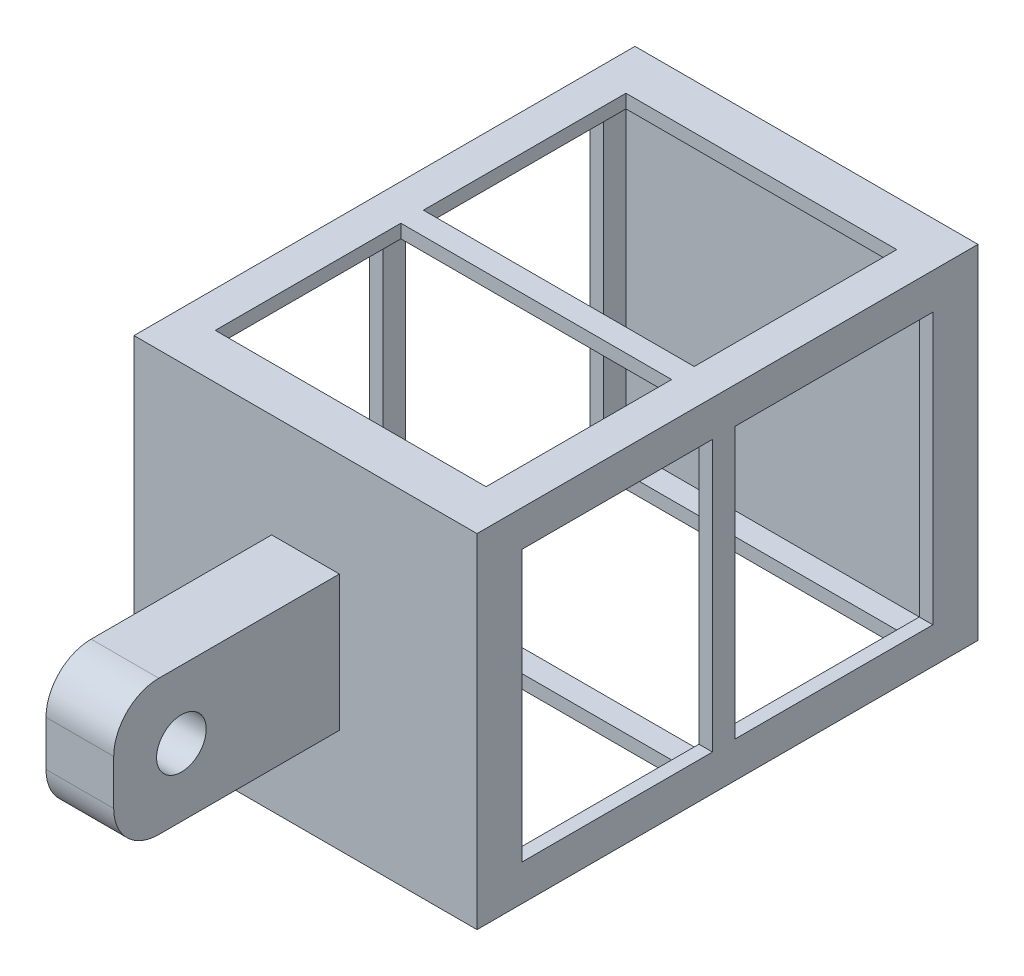
SolidWorks part; units mm, degrees
ref_plane "Plan de face" through (0, 0, 0) normal (0, 0, 1) x (1, 0, 0)
ref_plane "Plan de dessus" through (0, 0, 0) normal (0, 1, 0) x (1, 0, 0)
ref_plane "Plan de droite" through (0, 0, 0) normal (1, 0, 0) x (0, 0, -1)
sketch "Esquisse1" plane through (0, 0, 0) normal (0, 0, 1) x (1, 0, 0)
  line L1 (-33.9569, 29.5307) -> (36.0431, 29.5307)
  line L2 (-33.9569, 29.5307) -> (-33.9569, -40.4693)
  line L3 (-33.9569, -40.4693) -> (36.0431, -40.4693)
  line L4 (36.0431, 29.5307) -> (36.0431, -40.4693)
  line L5 (-36.9569, 32.5307) -> (39.0431, 32.5307)
  line L6 (-36.9569, 32.5307) -> (-36.9569, -43.4693)
  line L7 (-36.9569, -43.4693) -> (39.0431, -43.4693)
  line L8 (39.0431, 32.5307) -> (39.0431, -43.4693)
  dimension "D1" = 70
  dimension "D2" = 70
  dimension "D3" = 3
  dimension "D4" = 3
  dimension "D5" = 3
  dimension "D6" = 3
extrude "Boss.-Extru.2" add sketch "Esquisse1" along normal blind 101
sketch "Esquisse2" plane through (0, 0, 101) normal (0, 0, 1) x (1, 0, 0)
  line L1 (-36.9569, 32.5307) -> (39.0431, 32.5307)
  line L2 (-36.9569, 32.5307) -> (-36.9569, -43.4693)
  line L3 (-36.9569, -43.4693) -> (39.0431, -43.4693)
  line L4 (39.0431, 32.5307) -> (39.0431, -43.4693)
extrude "Boss.-Extru.3" add sketch "Esquisse2" along normal blind 5
sketch "Esquisse3" plane through (0, 0, 0) normal (0, 0, -1) x (-1, 0, 0)
  line L1 (-39.0431, 32.5307) -> (36.9569, 32.5307)
  line L2 (-39.0431, 32.5307) -> (-39.0431, -43.4693)
  line L3 (-39.0431, -43.4693) -> (36.9569, -43.4693)
  line L4 (36.9569, 32.5307) -> (36.9569, -43.4693)
extrude "Boss.-Extru.4" add sketch "Esquisse3" along normal blind 5
sketch "Esquisse4" plane through (0, 32.5307, 0) normal (0, 1, 0) x (1, 0, 0)
  line L0 (36.0431, 0) -> (-33.9569, 0) construction
  line L1 (-28.9569, -5) -> (31.0431, -5)
  line L2 (-28.9569, -5) -> (-28.9569, -49.8788)
  line L3 (-28.9569, -49.8788) -> (31.0431, -49.8788)
  line L4 (31.0431, -5) -> (31.0431, -49.8788)
  line L5 (-28.9569, -54.8788) -> (31.0431, -54.8788)
  line L6 (-28.9569, -54.8788) -> (-28.9569, -96)
  line L7 (-28.9569, -96) -> (31.0431, -96)
  line L8 (31.0431, -54.8788) -> (31.0431, -96)
  line L9 (36.0431, -101) -> (-33.9569, -101) construction
  line L10 (-33.9569, -101) -> (-33.9569, 0) construction
  line L11 (36.0431, -101) -> (36.0431, 0) construction
  dimension "D1" = 5
  dimension "D2" = 5
  dimension "D3" = 5
  dimension "D4" = 5
  dimension "D5" = 5
  dimension "D6" = 5
  dimension "D7" = 5
extrude "Enlèv. mat.-Extru.1" cut sketch "Esquisse4" against normal blind 80
sketch "Esquisse5" plane through (-36.9569, 0, 0) normal (-1, 0, 0) x (0, 0, 1)
  line L0 (101, 29.5307) -> (0, 29.5307) construction
  line L1 (5, 24.5307) -> (48.8322, 24.5307)
  line L2 (5, 24.5307) -> (5, -35.4693)
  line L3 (5, -35.4693) -> (48.8322, -35.4693)
  line L4 (48.8322, 24.5307) -> (48.8322, -35.4693)
  line L5 (53.8322, 24.5307) -> (96, 24.5307)
  line L6 (53.8322, 24.5307) -> (53.8322, -35.4693)
  line L7 (53.8322, -35.4693) -> (96, -35.4693)
  line L8 (96, 24.5307) -> (96, -35.4693)
  line L9 (101, -40.4693) -> (0, -40.4693) construction
  line L10 (0, 29.5307) -> (0, -40.4693) construction
  line L11 (101, 29.5307) -> (101, -40.4693) construction
  dimension "D1" = 5
  dimension "D2" = 5
  dimension "D3" = 5
  dimension "D4" = 5
  dimension "D5" = 5
  dimension "D6" = 5
  dimension "D7" = 5
extrude "Enlèv. mat.-Extru.2" cut sketch "Esquisse5" against normal blind 80
sketch "Esquisse8" plane through (0, 0, 106) normal (0, 0, 1) x (1, 0, 0)
  line L1 (-6.4569, 9.5307) -> (8.5431, 9.5307)
  line L2 (-6.4569, 9.5307) -> (-6.4569, -20.4693)
  line L3 (-6.4569, -20.4693) -> (8.5431, -20.4693)
  line L4 (8.5431, 9.5307) -> (8.5431, -20.4693)
  line L5 (-36.9569, -43.4693) -> (39.0431, -43.4693) construction
  line L6 (39.0431, -43.4693) -> (39.0431, 32.5307) construction
  line L7 (39.0431, 32.5307) -> (-36.9569, 32.5307) construction
  dimension "D1" = 15
  dimension "D2" = 30
  dimension "D3" = 23
  dimension "D4" = 23
  dimension "D5" = 30.5
extrude "Boss.-Extru.6" add sketch "Esquisse8" along normal blind 50
fillet "Congé6" radius 10 1 edges at (1.0431, -20.4693, 156)
fillet "Congé7" radius 10 1 edges at (1.0431, 9.5307, 156)
sketch "Esquisse10" plane through (-6.4569, 0, 0) normal (-1, 0, 0) x (0, 0, 1)
  line L0 (156, -0.4693) -> (156, -10.4693) construction
  line L1 (146, 9.5307) -> (106, 9.5307) construction
  line L2 (146, -20.4693) -> (106, -20.4693) construction
  circle A0 centre (141, -5.4693) radius 5.5
  dimension "D1" = 15
  dimension "D2" = 15
  dimension "D3" = 15
  dimension "D4" = 11
extrude "Enlèv. mat.-Extru.3" cut sketch "Esquisse10" against normal blind 25
sketch "Esquisse11" plane through (-6.4569, 0, 0) normal (-1, 0, 0) x (0, 0, 1)
  circle A0 centre (141, -5.4693) radius 7.5
extrude "Enlèv. mat.-Extru.4" cut sketch "Esquisse11" against normal blind 1
